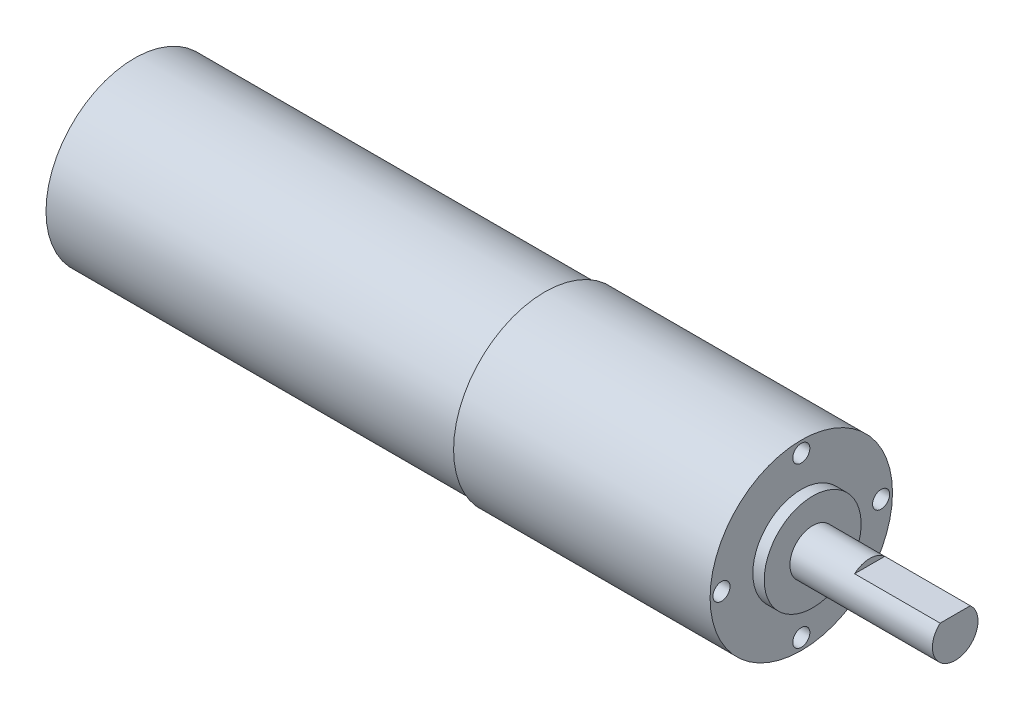
SolidWorks part; units mm, degrees
ref_plane "Front Plane" through (0, 0, 0) normal (0, 0, 1) x (1, 0, 0)
ref_plane "Top Plane" through (0, 0, 0) normal (0, 1, 0) x (1, 0, 0)
ref_plane "Right Plane" through (0, 0, 0) normal (1, 0, 0) x (0, 0, -1)
sketch "Sketch1" plane through (0, 0, 0) normal (0, 0, 1) x (1, 0, 0)
  line L0 (0, 0) -> (0, 15.5)
  line L1 (0, 15.5) -> (72, 15.5)
  line L2 (72, 15.5) -> (72, 16)
  line L3 (72, 16) -> (117, 16)
  line L4 (117, 16) -> (117, 8.5)
  line L5 (117, 8.5) -> (119, 8.5)
  line L6 (119, 8.5) -> (119, 4)
  line L7 (119, 4) -> (144, 4)
  line L8 (144, 4) -> (144, 0)
  line L9 (0, 0) -> (144, 0) construction
  line L10 (0, 0) -> (144, 0)
  point P12 (-1.9833, 0)
  point P13 (77.7216, 15.5)
  point P14 (77.6657, 16)
  point P15 (144, 0)
  point P16 (144, 0)
  point P17 (0, 0)
  point P18 (0, 0)
  point P19 (144, 0)
  point P20 (0, 0)
  point P21 (142.4388, 0)
  dimension "D1" = 31
  dimension "D2" = 32
  dimension "D3" = 72
  dimension "D4" = 45
  dimension "D5" = 17
  dimension "D6" = 8
  dimension "D7" = 2
  dimension "D8" = 25
revolve "Revolve1" add sketch "Sketch1" angle 360 about L9
sketch "Sketch2" plane through (144, 0, 0) normal (1, 0, 0) x (0, 0, -1)
  line L0 (-2.6458, 3) -> (2.6458, 3)
  arc A0 (2.6458, 3) -> (-2.6458, 3) centre (0, 0) ccw
  circle A1 centre (0, 0) radius 4 construction
  point P1 (0, 0)
  point P10 (0, 0)
  dimension "D1" = 3
extrude "Cut-Extrude1" cut sketch "Sketch2" against normal blind 15
sketch "Sketch3" plane through (117, 0, 0) normal (1, 0, 0) x (0, 0, -1)
  circle A0 centre (0, 0) radius 14 construction
  circle A1 centre (0, 14) radius 1.5
  circle A3 centre (14, 0) radius 1.5
  circle A4 centre (0, -14) radius 1.5
  circle A5 centre (-14, 0) radius 1.5
  point P5 (0, 0)
  point P6 (-14, 0)
  point P14 (0, 0)
  dimension "D1" = 28
  dimension "D2" = 3
  dimension "D3" = 4
extrude "Cut-Extrude2" cut sketch "Sketch3" against normal blind 5
